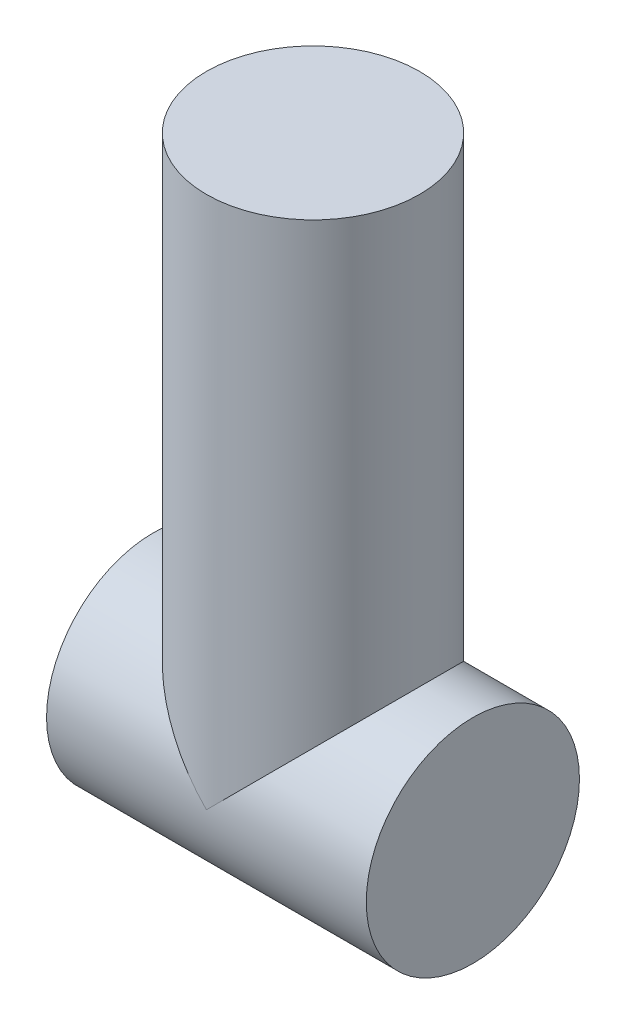
SolidWorks part; units mm, degrees
ref_plane "前视基准面" through (0, 0, 0) normal (0, 0, 1) x (1, 0, 0)
ref_plane "上视基准面" through (0, 0, 0) normal (0, 1, 0) x (1, 0, 0)
ref_plane "右视基准面" through (0, 0, 0) normal (1, 0, 0) x (0, 0, -1)
sketch "草图1" plane through (0, 0, 0) normal (0, 1, 0) x (1, 0, 0)
  circle A0 centre (0, 0) radius 20
  dimension "D1" = 40
extrude "凸台-拉伸1" add sketch "草图1" along normal blind 100
sketch "草图2" plane through (0, 0, 0) normal (1, 0, 0) x (0, 0, -1)
  line L0 (20, 0) -> (20, 100) construction
  circle A0 centre (0, 0) radius 20
extrude "凸台-拉伸2" add sketch "草图2" along normal mid plane 60
